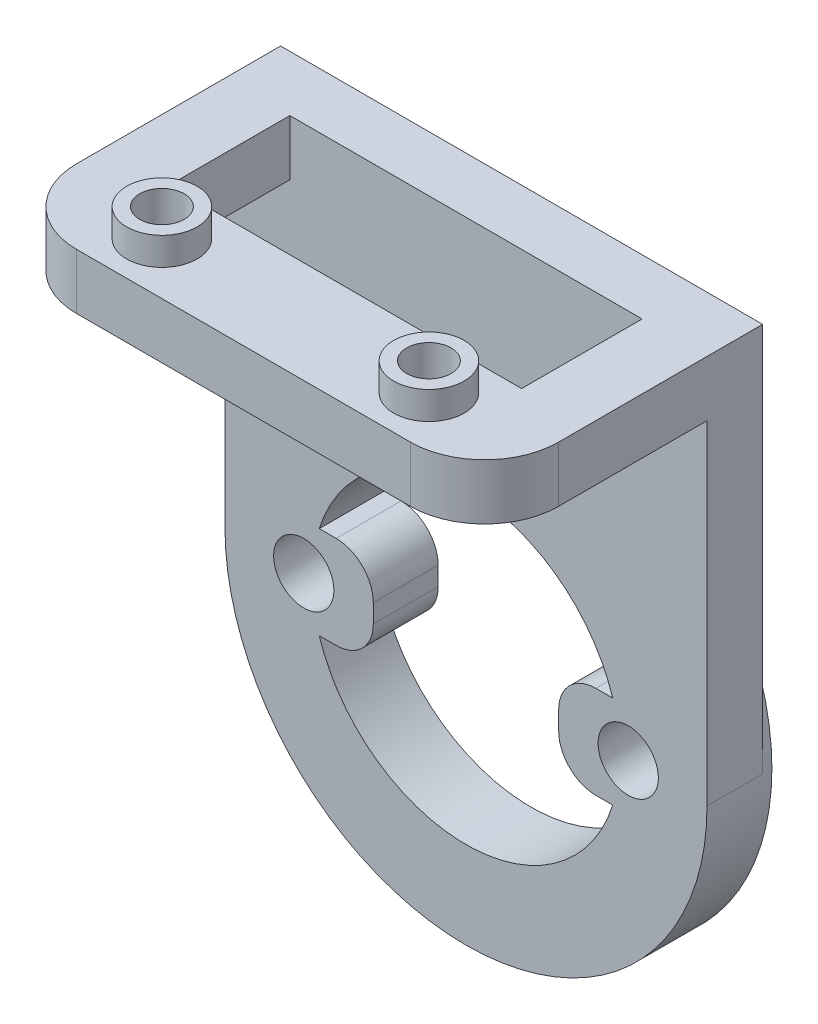
SolidWorks part; units mm, degrees
ref_plane "Plano frontal" through (0, 0, 0) normal (0, 0, 1) x (1, 0, 0)
ref_plane "Plano superior" through (0, 0, 0) normal (0, 1, 0) x (1, 0, 0)
ref_plane "Plano direito" through (0, 0, 0) normal (1, 0, 0) x (0, 0, -1)
sketch "Esboço1" plane through (0, 0, 0) normal (0, 0, 1) x (1, 0, 0)
  circle A0 centre (0, 0) radius 13
  circle A1 centre (0, 0) radius 8.3
  dimension "D1" = 26
  dimension "D2" = 16.6
extrude "Ressalto-extrusão1" add sketch "Esboço1" along normal blind 3.5
sketch "Esboço3" plane through (0, 0, 3.5) normal (0, 0, 1) x (1, 0, 0)
  line L0 (0, 8.3) -> (0, -8.3) construction
  line L1 (-8.124, 2.5) -> (-5, 2.5)
  line L3 (-8.124, -2.5) -> (-5, -2.5)
  line L4 (-5, 2.5) -> (-5, -2.5)
  line L5 (5, 2.5) -> (5, -2.5)
  line L6 (8.124, -2.5) -> (5, -2.5)
  line L7 (8.124, 2.5) -> (5, 2.5)
  arc A1 (-8.124, 2.5) -> (-8.124, -2.5) centre (0, 0) ccw
  circle A2 centre (0, 0) radius 8.3 construction
  arc A3 (8.124, 2.5) -> (8.124, -2.5) centre (0, 0) cw
  dimension "D1" = 2.5
  dimension "D2" = 2.5
  dimension "D3" = 5
extrude "Ressalto-extrusão2" add sketch "Esboço3" against normal through all
sketch "Esboço4" plane through (0, 0, 3.5) normal (0, 0, 1) x (1, 0, 0)
  line L0 (0, 13) -> (0, -13) construction
  circle A0 centre (-8.75, 0) radius 1.625
  circle A1 centre (0, 0) radius 13 construction
  circle A2 centre (8.75, 0) radius 1.625
  dimension "D1" = 3.25
  dimension "D2" = 8.75
extrude "Corte-extrusão2" cut sketch "Esboço4" against normal through all
fillet "Filete1" radius 2 4 edges at (5, -2.5, 1.75) (5, 2.5, 1.75) (-5, -2.5, 1.75) (-5, 2.5, 1.75)
sketch "Esboço7" plane through (0, 0, 3.5) normal (0, 0, 1) x (1, 0, 0)
  line L0 (-13, 0) -> (-13, 21)
  line L3 (-13, 21) -> (13, 21)
  line L5 (0, 0) -> (0, 18) construction
  line L6 (-13, 21) -> (0, 0) construction
  line L7 (13, 0) -> (13, 21)
  line L8 (0, 0) -> (13, 21) construction
  arc A1 (13, 0) -> (-13, 0) centre (0, 0) ccw
  point P1 (0, 21)
  dimension "D4" = 13
  dimension "D1" = 21
  dimension "D2" = 26
  dimension "D3" = 0
  dimension "D5" = 0
  dimension "D6" = 0
extrude "Ressalto-extrusão4" add sketch "Esboço7" against normal blind 3
sketch "Esboço8" plane through (0, 21, 0) normal (0, 1, 0) x (1, 0, 0)
  line L0 (-13, -3.5) -> (-13, -15.5)
  line L1 (-13, -15.5) -> (13, -15.5)
  line L2 (13, -15.5) -> (13, -3.5)
  line L3 (13, -3.5) -> (9.5, -3.5)
  line L4 (13, -3.5) -> (-13, -3.5) construction
  line L5 (9.5, -3.5) -> (9.5, -10)
  line L6 (9.5, -10) -> (-9.5, -10)
  line L7 (-9.5, -10) -> (-9.5, -3.5)
  line L8 (-9.5, -3.5) -> (-13, -3.5)
  dimension "D1" = 3.5
  dimension "D2" = 3.5
  dimension "D3" = 6.5
  dimension "D4" = 5.5
extrude "Ressalto-extrusão5" add sketch "Esboço8" against normal blind 3
sketch "Esboço9" plane through (0, 21, 0) normal (0, 1, 0) x (1, 0, 0)
  line L0 (0, 0) -> (0, -15.5) construction
  line L1 (13, 0) -> (-13, 0) construction
  line L2 (-13, -15.5) -> (13, -15.5) construction
  circle A0 centre (-7.2, -12.7) radius 1.9
  circle A1 centre (7.2, -12.7) radius 1.9
  dimension "D1" = 7.2
  dimension "D2" = 3.8
  dimension "D3" = 2.8
extrude "Ressalto-extrusão6" add sketch "Esboço9" along normal blind 1.5
sketch "Esboço10" plane through (0, 22.5, 0) normal (0, 1, 0) x (1, 0, 0)
  circle A0 centre (-7.2, -12.7) radius 1.2
  circle A1 centre (7.2, -12.7) radius 1.2
  dimension "D1" = 2.4
  dimension "D2" = 2.4
extrude "Corte-extrusão3" cut sketch "Esboço10" against normal through all
sketch "Esboço11" plane through (0, 18, 0) normal (0, -1, 0) x (1, 0, 0)
  line L0 (0, 15.5) -> (0, 10) construction
  line L1 (-4.9483, 12.7) -> (-6.0742, 14.65)
  line L2 (-6.0742, 14.65) -> (-8.3258, 14.65)
  line L3 (-8.3258, 14.65) -> (-9.4517, 12.7)
  line L4 (-9.4517, 12.7) -> (-8.3258, 10.75)
  line L5 (-8.3258, 10.75) -> (-6.0742, 10.75)
  line L6 (-6.0742, 10.75) -> (-4.9483, 12.7)
  line L7 (-13, 15.5) -> (13, 15.5) construction
  line L8 (9.5, 10) -> (-9.5, 10) construction
  line L9 (6.0742, 10.75) -> (4.9483, 12.7)
  line L10 (8.3258, 10.75) -> (6.0742, 10.75)
  line L11 (9.4517, 12.7) -> (8.3258, 10.75)
  line L12 (8.3258, 14.65) -> (9.4517, 12.7)
  line L13 (6.0742, 14.65) -> (8.3258, 14.65)
  line L14 (4.9483, 12.7) -> (6.0742, 14.65)
  circle A0 centre (-7.2, 12.7) radius 1.95 construction
  circle A1 centre (7.2, 12.7) radius 1.95 construction
  dimension "D1" = 3.9
extrude "Corte-extrusão4" cut sketch "Esboço11" against normal blind 1.6
fillet "Filete2" radius 4 2 edges at (13, 19.5, 15.5) (-13, 19.5, 15.5)
